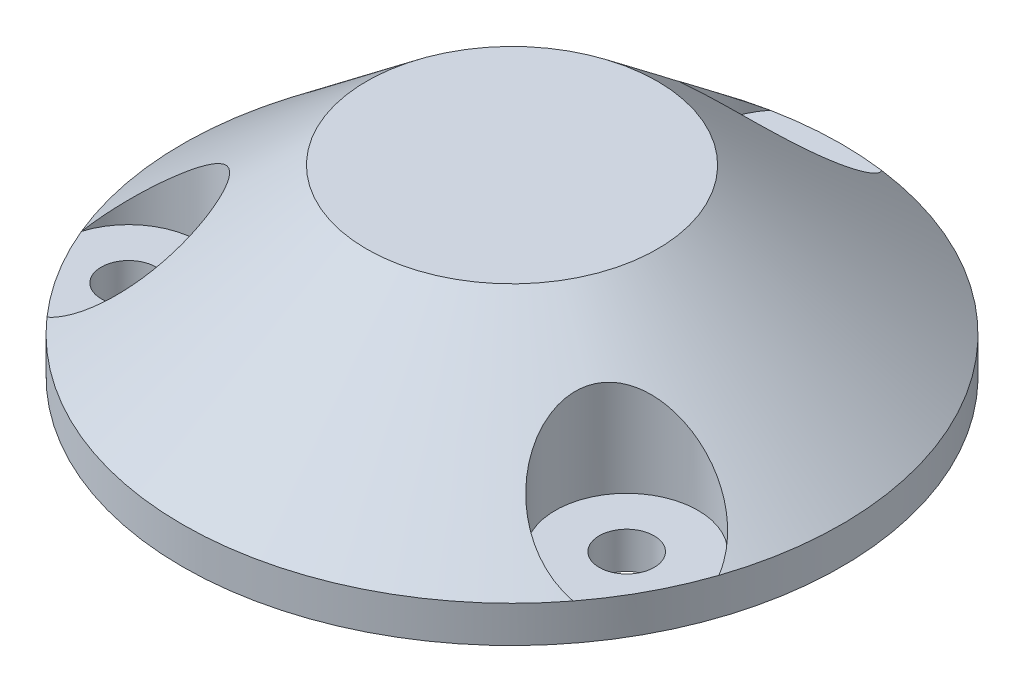
SolidWorks part; units mm, degrees
ref_plane "Plan de face" through (0, 0, 0) normal (0, 0, 1) x (1, 0, 0)
ref_plane "Plan de dessus" through (0, 0, 0) normal (0, 1, 0) x (1, 0, 0)
ref_plane "Plan de droite" through (0, 0, 0) normal (1, 0, 0) x (0, 0, -1)
sketch "Esquisse1" plane through (0, 0, 0) normal (0, 1, 0) x (1, 0, 0)
  circle A0 centre (0, 0) radius 9
  circle A1 centre (0, 0) radius 10.85
  dimension "D1" = 21.7
  dimension "D2" = 18
extrude "Boss.-Extru.1" add sketch "Esquisse1" along normal blind 7
sketch "Esquisse2" plane through (0, 7, 0) normal (0, 1, 0) x (1, 0, 0)
  circle A0 centre (0, 0) radius 18
  dimension "D1" = 36
extrude "Boss.-Extru.2" add sketch "Esquisse2" along normal blind 2
ref_plane "Plan1" through (0, 17, 0) normal (0, 1, 0) x (1, 0, 0)
sketch "Esquisse4" plane through (0, 9, 0) normal (0, 1, 0) x (1, 0, 0)
  circle A0 centre (0, 0) radius 18
extrude "Boss.-Extru.3" add sketch "Esquisse4" along normal blind 8 draft 51.5
sketch "Esquisse5" plane through (0, 7, 0) normal (0, -1, 0) x (1, 0, 0)
  circle A0 centre (-12.8987, 8.0413) radius 1.5
  circle A1 centre (0, 0) radius 18 construction
  circle A2 centre (13.4133, 7.15) radius 1.5
  circle A3 centre (-0.5146, -15.1913) radius 1.5
  point P10 (0, 0)
  dimension "D1" = 3
  dimension "D2" = 15.2
  dimension "D3" = 3
extrude "Enlèv. mat.-Extru.1" cut sketch "Esquisse5" against normal blind 4
sketch "Esquisse6" plane through (0, 17, 0) normal (0, 1, 0) x (1, 0, 0)
  circle A0 centre (-0.5146, 15.1913) radius 3.9
  circle A1 centre (13.4133, -7.15) radius 3.9
  circle A2 centre (-12.8987, -8.0413) radius 3.9
  point P10 (0, 0)
  dimension "D1" = 7.8
  dimension "D2" = 3
extrude "Enlèv. mat.-Extru.2" cut sketch "Esquisse6" against normal blind 8
sketch "Esquisse9" plane through (0, 0, 0) normal (0, -1, 0) x (1, 0, 0)
  circle A0 centre (0, 0) radius 10.85
extrude "Enlèv. mat.-Extru.4" cut sketch "Esquisse9" against normal up to surface (7 mm away) up to face at (-12.8987, 7, 6.5413)
sketch "Esquisse10" plane through (0, 7, 0) normal (0, -1, 0) x (1, 0, 0)
  circle A0 centre (0, 0) radius 9
  dimension "D1" = 18
extrude "Enlèv. mat.-Extru.5" cut sketch "Esquisse10" against normal blind 8
